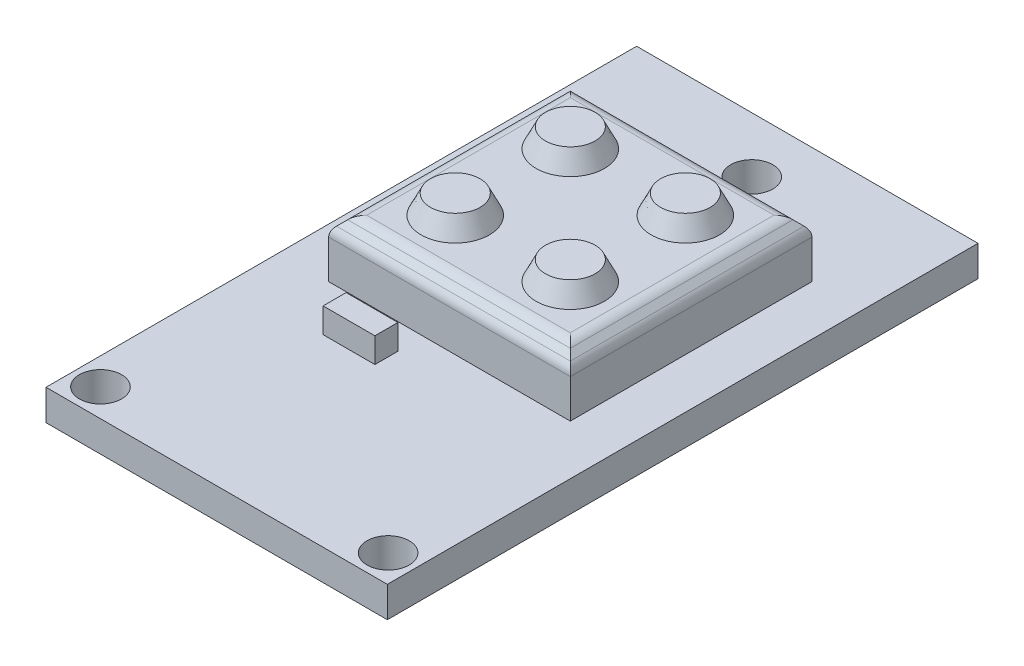
SolidWorks part; units mm, degrees
ref_plane "Front Plane" through (0, 0, 0) normal (0, 0, 1) x (1, 0, 0)
ref_plane "Top Plane" through (0, 0, 0) normal (0, 1, 0) x (1, 0, 0)
ref_plane "Right Plane" through (0, 0, 0) normal (1, 0, 0) x (0, 0, -1)
sketch "Sketch6" plane through (0, 0, 0) normal (0, 1, 0) x (1, 0, 0)
  line L1 (0, 0) -> (18, 0)
  line L2 (0, 0) -> (0, 31)
  line L3 (0, 31) -> (18, 31)
  line L4 (18, 0) -> (18, 31)
  circle A0 centre (9, 28) radius 1.1
  circle A1 centre (1.5, 1.54) radius 1.1
  circle A3 centre (16.5, 1.54) radius 1.1
  point P13 (9, 31)
  dimension "D3" = 2.2
  dimension "D1" = 18
  dimension "D2" = 31
  dimension "D4" = 1.5
  dimension "D5" = 1.54
  dimension "D6" = 1.5
  dimension "D7" = 3
sketch "Sketch1" plane through (0, 0, 0) normal (0, 1, 0) x (1, 0, 0)
  line L0 (9, 24.84) -> (9, 18.54) construction
  line L1 (2.7, 12.24) -> (15.3, 12.24)
  line L2 (2.7, 12.24) -> (2.7, 24.84)
  line L3 (2.7, 24.84) -> (15.3, 24.84)
  line L4 (15.3, 12.24) -> (15.3, 24.84)
  line L5 (9, 18.54) -> (15.3, 18.54) construction
  line L6 (0, 31) -> (18, 31) construction
  point P11 (9, 31)
  dimension "D1" = 12.46
  dimension "D2" = 12.6
extrude "Boss-Extrude1" add sketch "Sketch1" along normal blind 1.3
sketch "Sketch3" plane through (0, 1.3, 0) normal (0, 1, 0) x (1, 0, 0)
  line L0 (9, 24.84) -> (9, 12.24) construction
  line L1 (15.3, 24.84) -> (2.7, 24.84) construction
  line L2 (2.7, 12.24) -> (15.3, 12.24) construction
  line L4 (2.7, 24.84) -> (2.7, 12.24) construction
  line L5 (2.7, 18.54) -> (15.3, 18.54) construction
  line L6 (15.3, 12.24) -> (15.3, 24.84) construction
  circle A0 centre (6, 21.54) radius 0.7937 construction
  circle A1 centre (6, 21.54) radius 1.2938
  circle A2 centre (12, 21.54) radius 1.2938
  circle A3 centre (12, 21.54) radius 0.7937 construction
  circle A4 centre (12, 15.54) radius 1.2938
  circle A5 centre (12, 15.54) radius 0.7937 construction
  circle A6 centre (6, 15.54) radius 1.2938
  circle A7 centre (6, 15.54) radius 0.7937 construction
  dimension "D3" = 1.5875
  dimension "D4" = 0.5
  dimension "D1" = 3
  dimension "D2" = 3
extrude "Boss-Extrude3" add sketch "Sketch3" along normal blind 2.7
draft "Draft1" type of draft neutral plane draft angle 26 faces to draft 4 face at (6, 4, -16.8338) face at (12, 4, -14.2463) face at (12, 4, -22.8337) face at (6, 4, -20.2462) neutral plane through (6, 4, -21.54) neutral plane normal (0, 1, 0) parameters "D1"=26
sketch "Sketch4" plane through (0, 1.3, 0) normal (0, 1, 0) x (1, 0, 0)
  line L1 (2.7, 12.24) -> (15.3, 12.24)
  line L2 (2.7, 12.24) -> (2.7, 24.84)
  line L3 (2.7, 24.84) -> (15.3, 24.84)
  line L4 (15.3, 12.24) -> (15.3, 24.84)
extrude "Boss-Extrude4" add sketch "Sketch4" along normal blind 1.7
sketch "Sketch5" plane through (0, 0, 0) normal (0, -1, 0) x (1, 0, 0)
  line L0 (9, -12.24) -> (9, -18.54) construction
  line L5 (2.7, -12.24) -> (15.3, -12.24) construction
  line L6 (9, -18.54) -> (2.7, -18.54) construction
  line L7 (2.7, -24.84) -> (2.7, -12.24) construction
  line L8 (17.9, -15.5) -> (18, -15.5) construction
  line L9 (0.1, -30.9) -> (17.9, -30.9)
  line L10 (0.1, -30.9) -> (0.1, -0.1)
  line L11 (0.1, -0.1) -> (17.9, -0.1)
  line L12 (17.9, -30.9) -> (17.9, -0.1)
  line L13 (18, 0) -> (18, -31) construction
  line L14 (0.1, -15.5) -> (0, -15.5) construction
  line L15 (0, 0) -> (0, -31) construction
  line L16 (9, -0.1) -> (9, 0) construction
  line L17 (0, 0) -> (18, 0) construction
  line L18 (9, -30.9) -> (9, -31) construction
  line L19 (0, -31) -> (18, -31) construction
  dimension "D1" = 0.1
extrude "Boss-Extrude5" add sketch "Sketch5" along normal blind 1.6
fillet "Fillet1" radius 0.7 4 edges at (9, 3, -12.24) (15.3, 3, -18.54) (9, 3, -24.84) (2.7, 3, -18.54) profile chamfer
sketch "Sketch7" plane through (0, 0, 0) normal (0, 1, 0) x (1, 0, 0)
  circle A0 centre (1.5, 1.54) radius 1.1 construction
  circle A1 centre (9, 28) radius 1.1 construction
  circle A2 centre (16.5, 1.54) radius 1.1 construction
  circle A3 centre (1.5, 1.54) radius 1.1
  circle A4 centre (9, 28) radius 1.1
  circle A5 centre (16.5, 1.54) radius 1.1
extrude "Cut-Extrude1" cut sketch "Sketch7" against normal through all
sketch "Sketch8" plane through (0, 0, 0) normal (0, 1, 0) x (1, 0, 0)
  line L0 (6.3, 10.9) -> (6.3, 10.3) construction
  line L1 (4.95, 10.9) -> (7.65, 10.9)
  line L2 (4.95, 10.9) -> (4.95, 9.7)
  line L3 (4.95, 9.7) -> (7.65, 9.7)
  line L4 (7.65, 10.9) -> (7.65, 9.7)
  line L5 (6.3, 10.3) -> (7.65, 10.3) construction
  line L6 (0, 0) -> (0, 31) construction
  line L7 (0, 0) -> (18, 0) construction
  line L8 (4.95, 10.9) -> (4.95, 12.24) construction
  line L9 (4.95, 12.24) -> (7.65, 12.24) construction
  line L10 (2.7, 12.24) -> (15.3, 12.24) construction
  line L11 (7.65, 12.24) -> (7.65, 10.9) construction
  dimension "D1" = 6.3
  dimension "D2" = 10.3
  dimension "D3" = 1.2
  dimension "D4" = 2.7
extrude "capacitor" add sketch "Sketch8" along normal blind 1.3
fillet "Fillet5" radius 0.7 8 edges at (14.6, 3, -18.54) (15.3, 2.3, -18.54) (9, 2.3, -24.84) (9, 3, -24.14) (9, 3, -12.94) (9, 2.3, -12.24) (2.7, 2.3, -18.54) (3.4, 3, -18.54)
